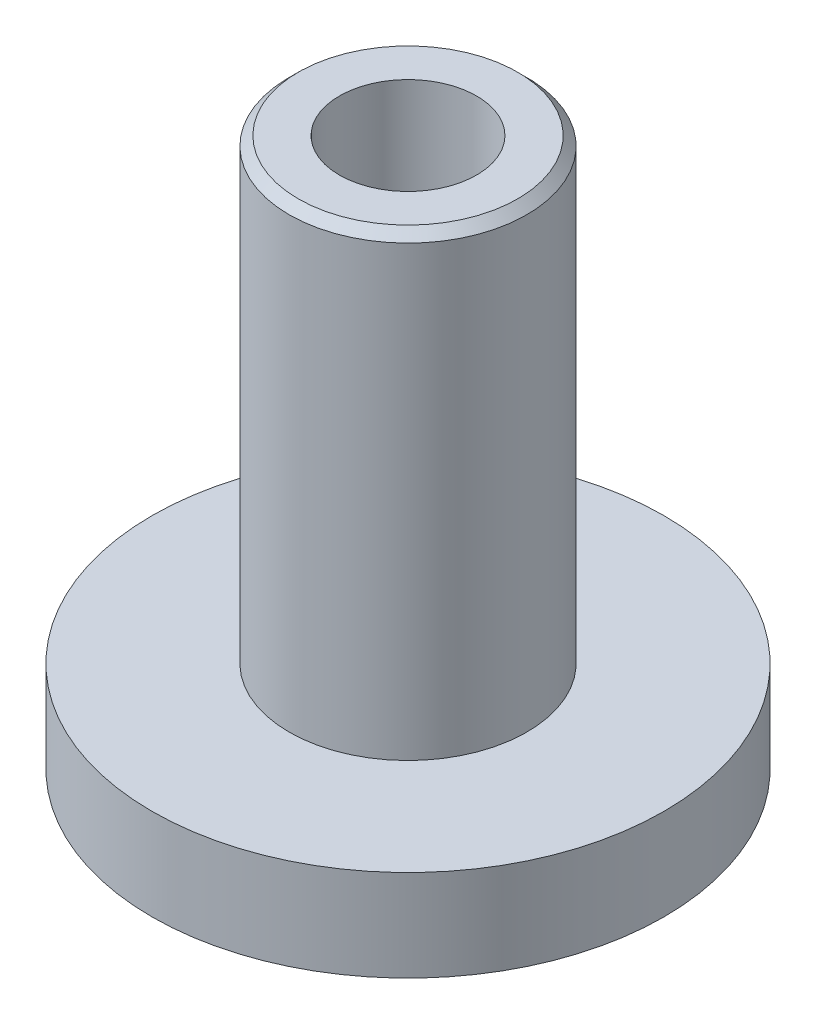
SolidWorks part; units mm, degrees
ref_plane "前视基准面" through (0, 0, 0) normal (0, 0, 1) x (1, 0, 0)
ref_plane "上视基准面" through (0, 0, 0) normal (0, 1, 0) x (1, 0, 0)
ref_plane "右视基准面" through (0, 0, 0) normal (1, 0, 0) x (0, 0, -1)
sketch "草图1" plane through (0, 0, 0) normal (0, 1, 0) x (1, 0, 0)
  circle A0 centre (0, 0) radius 28
  dimension "D1" = 56
extrude "凸台-拉伸1" add sketch "草图1" along normal blind 10 contours A0
sketch "草图2" plane through (0, 10, 0) normal (0, 1, 0) x (1, 0, 0)
  circle A0 centre (0, 0) radius 13
  circle A1 centre (0, 0) radius 7.5
  dimension "D1" = 26
  dimension "D2" = 15
extrude "凸台-拉伸2" add sketch "草图2" along normal blind 50 contours A1 | A0
chamfer "倒角1" distance 1 angle 45 1 edges at (0, 60, 13)
